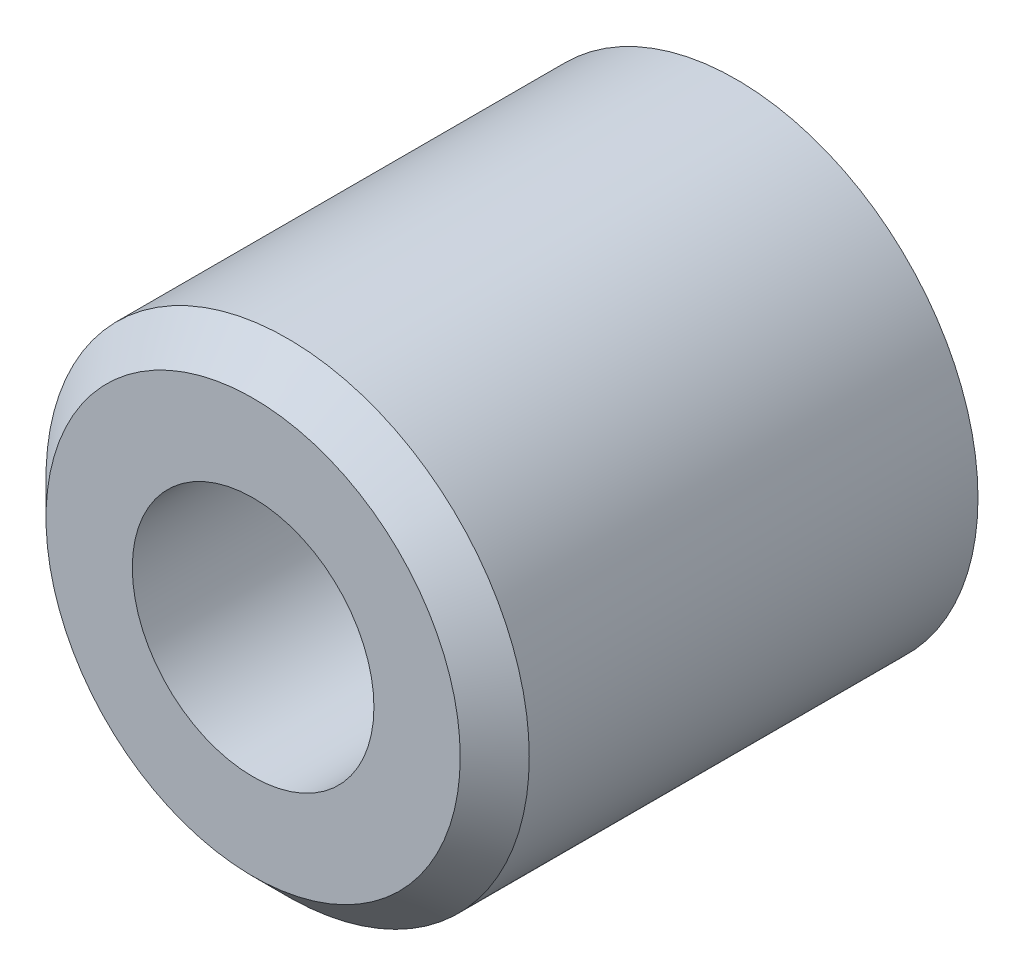
SolidWorks part; units mm, degrees
ref_plane "Спереди" through (0, 0, 0) normal (0, 0, 1) x (1, 0, 0)
ref_plane "Сверху" through (0, 0, 0) normal (0, 1, 0) x (1, 0, 0)
ref_plane "Справа" through (0, 0, 0) normal (1, 0, 0) x (0, 0, -1)
sketch "Эскиз1" plane through (0, 0, 0) normal (0, 0, 1) x (1, 0, 0)
  circle A0 centre (0, 0) radius 1.75
  circle A1 centre (0, 0) radius 3.5
  dimension "D1" = 3.5
  dimension "D2" = 7
extrude "Бобышка-Вытянуть1" add sketch "Эскиз1" along normal blind 7
chamfer "Фаска2" distance 0.5 angle 45 1 edges at (3.5, 0, 7)
